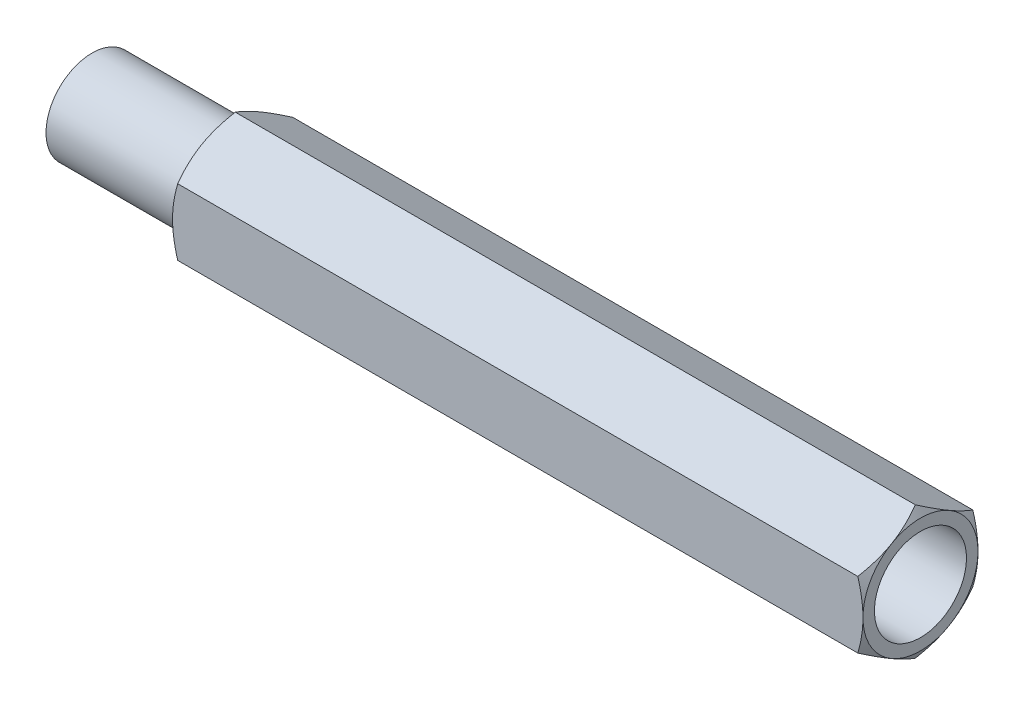
SolidWorks part; units mm, degrees
ref_plane "前视基准面" through (0, 0, 0) normal (0, 0, 1) x (1, 0, 0)
ref_plane "上视基准面" through (0, 0, 0) normal (0, 1, 0) x (1, 0, 0)
ref_plane "右视基准面" through (0, 0, 0) normal (1, 0, 0) x (0, 0, -1)
sketch "草图1" plane through (0, 0, 0) normal (0, 0, 1) x (1, 0, 0)
  line L0 (0, 0) -> (36, 0) construction
  line L1 (0, 0) -> (0, 1)
  line L2 (0, 1) -> (6, 1)
  line L3 (6, 0) -> (6, 18.45)
  line L4 (6, 18.45) -> (36, 18.45)
  line L5 (36, 18.45) -> (36, 0)
  line L6 (36, 1) -> (4, 1)
  line L7 (4, 1) -> (4, 0)
  line L10 (5, 1) -> (5, 0)
  line L11 (4, 6.9175) -> (0.0062, 0)
  line L15 (36, 6.9175) -> (4, 6.9175)
  line L16 (0, 6.9175) -> (5, 6.9175)
  line L17 (36, 1) -> (42, 1)
  line L18 (42, 1) -> (42, 0)
  line L19 (42, 0) -> (36, 0)
  line L20 (13.5, 1) -> (13.5, 0)
  point P20 (36, 0.6)
  point P24 (0, 0.6)
  point P33 (66, 0)
  dimension "D1" = 13.835
  dimension "M" = 2
  dimension "L" = 30
  dimension "D2" = 13.835
  dimension "F" = 6
  dimension "D3" = 60
  dimension "N" = 2
  dimension "D4" = 28.5
  dimension "PM" = 0.4
  dimension "PN" = 0.4
  dimension "C" = 36.9
  dimension "A" = 1
  dimension "2N" = 32
  dimension "15N" = 24
  dimension "G" = 6
sketch "草图2" plane through (0, 0, 0) normal (1, 0, 0) x (0, 0, -1)
  line L0 (-2.5, 0) -> (2.5, 0) construction
  line L1 (0, 2.8868) -> (-2.5, 1.4434)
  line L2 (-2.5, 1.4434) -> (-2.5, -1.4434)
  line L3 (-2.5, -1.4434) -> (0, -2.8868)
  line L4 (0, -2.8868) -> (2.5, -1.4434)
  line L5 (2.5, -1.4434) -> (2.5, 1.4434)
  line L6 (2.5, 1.4434) -> (0, 2.8868)
  line L7 (0, 2.8868) -> (0, -2.8868) construction
  circle A0 centre (0, 0) radius 2.5 construction
  point P11 (0, -2.9)
  dimension "C" = 5.8
  dimension "B" = 5
sketch "草图3" plane through (0, 0, 0) normal (1, 0, 0) x (0, 0, -1)
  line L0 (2.5, 1.4434) -> (0, 2.8868) construction
  line L1 (0, 2.8868) -> (-2.5, 1.4434) construction
  line L2 (-2.5, 1.4434) -> (-2.5, -1.4434) construction
  line L3 (0, -2.8868) -> (2.5, -1.4434) construction
  line L4 (2.5, -1.4434) -> (2.5, 1.4434) construction
  line L5 (-2.5, -1.4434) -> (0, -2.8868) construction
  line L6 (2.5, 1.4434) -> (0, 2.8868)
  line L7 (0, 2.8868) -> (-2.5, 1.4434)
  line L8 (-2.5, 1.4434) -> (-2.5, -1.4434)
  line L9 (0, -2.8868) -> (2.5, -1.4434)
  line L10 (2.5, -1.4434) -> (2.5, 1.4434)
  line L11 (-2.5, -1.4434) -> (0, -2.8868)
extrude "凸台-拉伸1" add sketch "草图3" along normal up to vertex (36 mm away) from vertex at 6 starting at point (6, 18.45, 0)
sketch "草图4" plane through (6, 0, 0) normal (-1, 0, 0) x (0, 0, 1)
  circle A0 centre (0, 0) radius 2.5
  circle A1 centre (0, 0) radius 32
  circle A2 centre (0, 0) radius 2.5 construction
  dimension "D1" = 64
extrude "切除-拉伸1" cut sketch "草图4" against normal blind 2 draft 60
sketch "草图5" plane through (36, 0, 0) normal (1, 0, 0) x (0, 0, -1)
  circle A1 centre (0, 0) radius 32
  circle A2 centre (0, 0) radius 32
  circle A3 centre (0, 0) radius 2.5
  circle A4 centre (0, 0) radius 2.5
  dimension "D1" = 0
  dimension "D2" = 0
extrude "切除-拉伸2" cut sketch "草图5" against normal blind 2 draft 60
sketch "草图6" plane through (0, 0, 0) normal (0, 0, 1) x (1, 0, 0)
  line L0 (6, 0) -> (6, 2)
  line L1 (6, 0) -> (6, 18.45) construction
  line L2 (0, 0) -> (6, 0)
  line L3 (6, 2) -> (0, 2)
  line L4 (0, 2) -> (0, 0)
  dimension "D1" = 2
revolve "旋转1" add sketch "草图6" angle 360 mid plane about L2
sketch "Sketch1" plane through (36, 0, 0) normal (1, 0, 0) x (0, 0, -1)
  circle A0 centre (0, 0) radius 2
  dimension "D1" = 4
extrude "Extrude1" cut sketch "Sketch1" against normal blind 15
